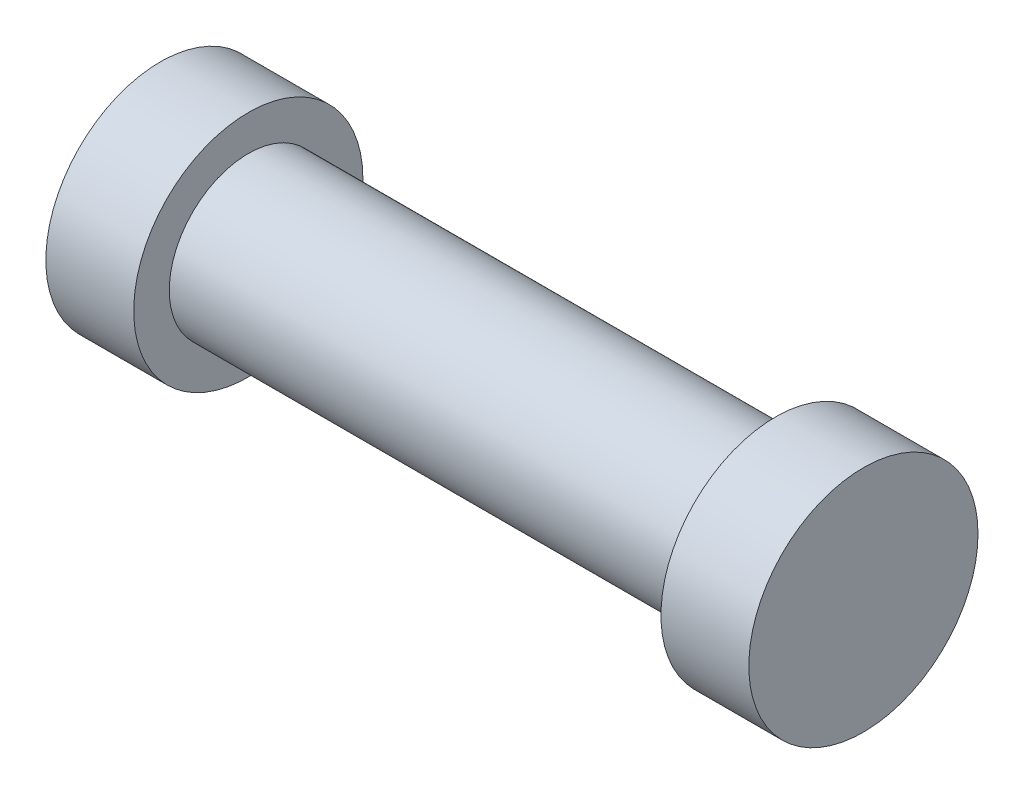
SolidWorks part; units mm, degrees
ref_plane "Front Plane" through (0, 0, 0) normal (0, 0, 1) x (1, 0, 0)
ref_plane "Top Plane" through (0, 0, 0) normal (0, 1, 0) x (1, 0, 0)
ref_plane "Right Plane" through (0, 0, 0) normal (1, 0, 0) x (0, 0, -1)
sketch "Sketch1" plane through (0, 0, 0) normal (1, 0, 0) x (0, 0, -1)
  circle A0 centre (0, 0) radius 0.9
  dimension "D1" = 1.8
extrude "Boss-Extrude1" add sketch "Sketch1" along normal mid plane 6
sketch "Sketch2" plane through (3, 0, 0) normal (1, 0, 0) x (0, 0, -1)
  circle A0 centre (0, 0) radius 1.304
extrude "Boss-Extrude2" add sketch "Sketch2" along normal blind 1
mirror "Mirror1" about plane through (0, 0, 0) normal (1, 0, 0) of "Boss-Extrude2"
